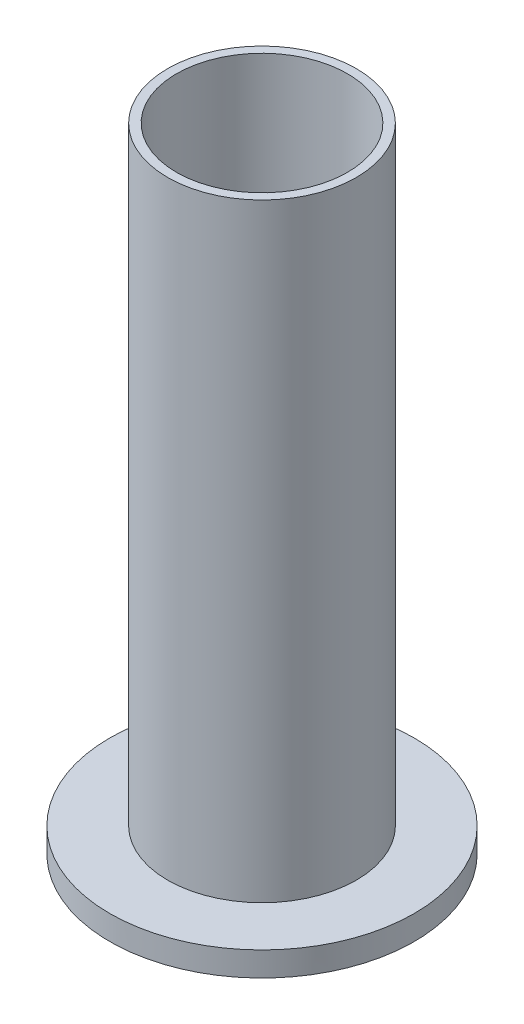
SolidWorks part; units mm, degrees
ref_plane "Front Plane" through (0, 0, 0) normal (0, 0, 1) x (1, 0, 0)
ref_plane "Top Plane" through (0, 0, 0) normal (0, 1, 0) x (1, 0, 0)
ref_plane "Right Plane" through (0, 0, 0) normal (1, 0, 0) x (0, 0, -1)
sketch "Sketch1" plane through (0, 0, 0) normal (0, 1, 0) x (1, 0, 0)
  line L1 (-50.8, -50.8) -> (50.8, -50.8)
  line L2 (-50.8, -50.8) -> (-50.8, 50.8)
  line L3 (-50.8, 50.8) -> (50.8, 50.8)
  line L4 (50.8, -50.8) -> (50.8, 50.8)
  line L5 (-50.8, -50.8) -> (50.8, 50.8) construction
  line L6 (-50.8, 50.8) -> (50.8, -50.8) construction
  point P0 (0, 0)
  dimension "D1" = 101.6
extrude "Boss-Extrude1" add sketch "Sketch1" along normal blind 10
sketch "Sketch2" plane through (0, 0, 0) normal (0, -1, 0) x (-1, 0, 0)
  circle A0 centre (0, 0) radius 5
  dimension "D1" = 10
extrude "Cut-Extrude1" cut sketch "Sketch2" against normal blind 5
sketch "Sketch3" plane through (0, 10, 0) normal (0, 1, 0) x (1, 0, 0)
  circle A0 centre (0, 0) radius 12.5
  dimension "D1" = 25
extrude "Boss-Extrude2" add sketch "Sketch3" along normal blind 2
sketch "Sketch4" plane through (0, 12, 0) normal (0, 1, 0) x (1, 0, 0)
  circle A0 centre (0, 0) radius 7.75
  dimension "D1" = 15.5
extrude "Boss-Extrude3" add sketch "Sketch4" along normal blind 50
sketch "Sketch6" plane through (0, 10, 0) normal (0, 1, 0) x (1, 0, 0)
  line L1 (50.8, 50.8) -> (-50.8, 50.8)
  line L2 (50.8, 50.8) -> (50.8, -50.8)
  line L3 (50.8, -50.8) -> (-50.8, -50.8)
  line L4 (-50.8, 50.8) -> (-50.8, -50.8)
extrude "Cut-Extrude2" cut sketch "Sketch6" against normal blind 10
sketch "Sketch7" plane through (0, 62, 0) normal (0, 1, 0) x (1, 0, 0)
  circle A0 centre (0, 0) radius 7.0239
  dimension "D1" = 14.0478
extrude "Cut-Extrude3" cut sketch "Sketch7" against normal blind 30
